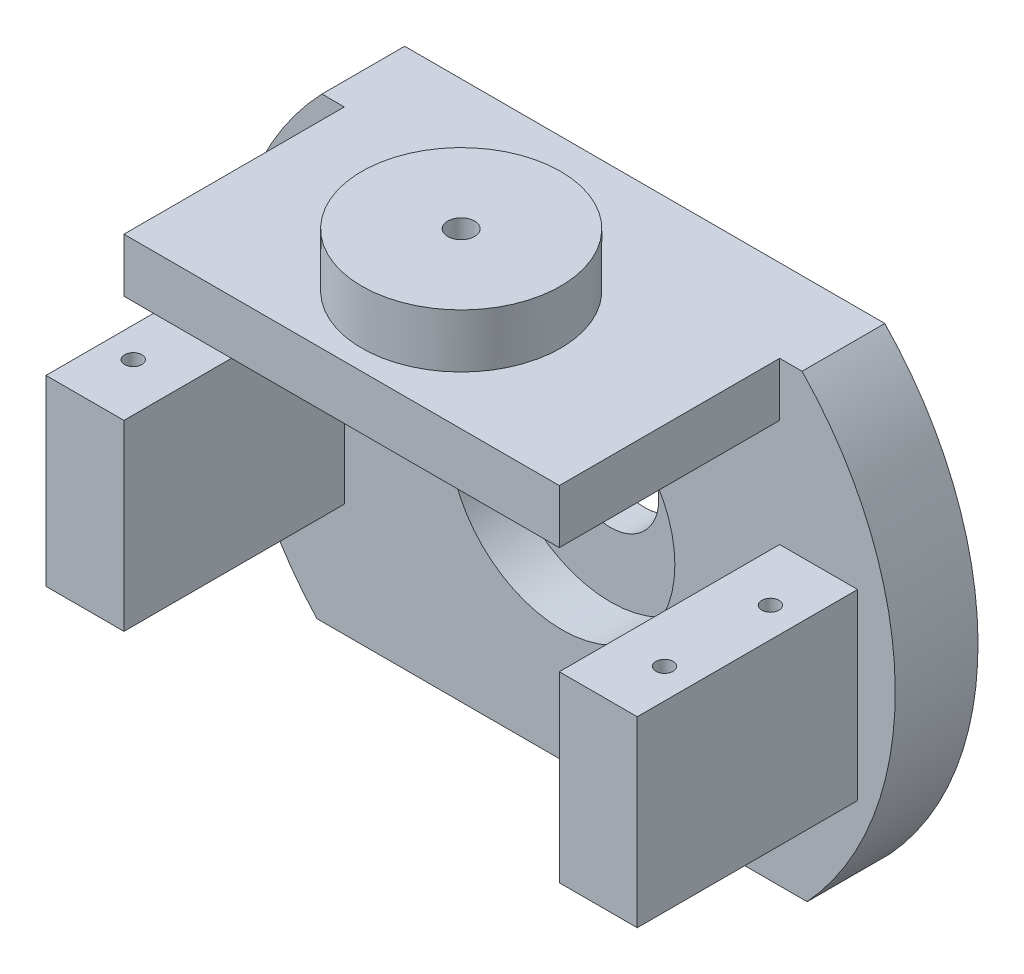
SolidWorks part; units mm, degrees
ref_plane "Plan de face" through (0, 0, 0) normal (0, 0, 1) x (1, 0, 0)
ref_plane "Plan de dessus" through (0, 0, 0) normal (0, 1, 0) x (1, 0, 0)
ref_plane "Plan de droite" through (0, 0, 0) normal (1, 0, 0) x (0, 0, -1)
sketch "Esquisse1" plane through (0, 0, 0) normal (0, 0, 1) x (1, 0, 0)
  line L1 (-27.5, 21.5) -> (27.5, 21.5)
  line L2 (-27.5, 21.5) -> (-27.5, -21.5)
  line L3 (-27.5, -21.5) -> (27.5, -21.5)
  line L4 (27.5, 21.5) -> (27.5, -21.5)
  line L5 (-27.5, 21.5) -> (27.5, -21.5) construction
  line L6 (-27.5, -21.5) -> (27.5, 21.5) construction
  point P0 (0, 0)
  dimension "D1" = 55
  dimension "D2" = 43
extrude "Boss.-Extru.1" add sketch "Esquisse1" along normal blind 27
sketch "Esquisse2" plane through (0, -21.5, 0) normal (0, -1, 0) x (1, 0, 0)
  line L0 (27.5, 27) -> (27.5, 0) construction
  line L1 (-27.5, 0) -> (27.5, 0) construction
  line L2 (-27.5, 0) -> (-27.5, 6.5) construction
  line L3 (-27.5, 6.5) -> (27.5, 6.5) construction
  line L4 (27.5, 0) -> (27.5, 6.5) construction
  line L5 (0, 0) -> (0, 33.905) construction
  line L6 (-20.25, 6.5) -> (20.25, 6.5)
  line L7 (-20.25, 6.5) -> (-20.25, 28.1766)
  line L8 (-20.25, 28.1766) -> (20.25, 28.1766)
  line L9 (20.25, 6.5) -> (20.25, 28.1766)
  dimension "D1" = 6.5
  dimension "D2" = 40.5
extrude "Enlèv. mat.-Extru.1" cut sketch "Esquisse2" against normal offset from surface (38 mm away) 5 up to face at (0, 21.5, 13.5)
sketch "Esquisse3" plane through (0, -21.5, 0) normal (0, -1, 0) x (1, 0, 0)
  line L0 (-20.25, 16.75) -> (28.5647, 16.75) construction
  line L1 (-20.25, 6.5) -> (-20.25, 27) construction
  line L2 (0, 27) -> (0, -2.6321) construction
  line L3 (-20.25, 27) -> (20.25, 27) construction
  line L4 (-20.25, 27) -> (-20.25, 6.5) construction
  circle A0 centre (-24.71, 21.675) radius 0.7
  circle A2 centre (-24.71, 11.825) radius 0.7
  circle A3 centre (24.71, 11.825) radius 0.7
  circle A4 centre (24.71, 21.675) radius 0.7
  point P9 (-24.71, 21.675)
  point P12 (-24.71, 11.825)
  point P13 (24.71, 11.825)
  point P14 (24.71, 21.675)
  dimension "D4" = 1.4
  dimension "D1" = 4.46
  dimension "D2" = 4.925
  dimension "D3" = 9.85
extrude "Enlèv. mat.-Extru.2" cut sketch "Esquisse3" against normal up to surface (43 mm away) up to face at (0, 21.5, 13.5)
sketch "Esquisse4" plane through (0, -21.5, 0) normal (0, -1, 0) x (1, 0, 0)
  line L0 (27.5, 27) -> (27.5, 0) construction
  line L1 (-27.5, 27) -> (27.5, 27)
  line L2 (-27.5, 27) -> (-27.5, 6.5)
  line L3 (-27.5, 6.5) -> (27.5, 6.5)
  line L4 (27.5, 27) -> (27.5, 6.5)
extrude "Enlèv. mat.-Extru.3" cut sketch "Esquisse4" against normal offset from surface (11 mm away) 27 up to face at (0, 16.5, 16.75)
sketch "Esquisse5" plane through (-27.5, 0, 0) normal (-1, 0, 0) x (0, 0, 1)
  line L6 (6.5, 16.5) -> (27, 16.5)
  line L7 (6.5, 16.5) -> (6.5, 6.5)
  line L8 (6.5, 6.5) -> (27, 6.5)
  line L9 (27, 16.5) -> (27, 6.5)
  line L10 (27, 21.5) -> (27, -10.5) construction
  line L11 (27, 21.5) -> (0, 21.5) construction
  line L13 (6.5, -10.5) -> (6.5, -21.5) construction
  point P4 (0, 0)
  point P12 (0, 0)
  dimension "D1" = 5
  dimension "D2" = 10
extrude "Enlèv. mat.-Extru.6" cut sketch "Esquisse5" against normal up to surface (55 mm away) up to face at (27.5, -3.5, 11.1667)
sketch "Esquisse6" plane through (0, 16.5, 0) normal (0, -1, 0) x (1, 0, 0)
  line L1 (-27.5, 27) -> (-20.25, 27)
  line L2 (-27.5, 27) -> (-27.5, 6.5)
  line L3 (-27.5, 6.5) -> (-20.25, 6.5)
  line L4 (-20.25, 27) -> (-20.25, 6.5)
  line L5 (20.25, 27) -> (27.5, 27)
  line L6 (20.25, 27) -> (20.25, 6.5)
  line L7 (20.25, 6.5) -> (27.5, 6.5)
  line L8 (27.5, 27) -> (27.5, 6.5)
extrude "Enlèv. mat.-Extru.7" cut sketch "Esquisse6" against normal up to surface (5 mm away) up to face at (24.71, 21.5, 20.975)
sketch "Esquisse7" plane through (0, 0, 0) normal (0, 0, -1) x (-1, 0, 0)
  circle A0 centre (0, 0) radius 31
  dimension "D1" = 62
extrude "Boss.-Extru.2" add sketch "Esquisse7" against normal up to surface (6.5 mm away) up to face at (0, 3.75, 6.5)
sketch "Esquisse8" plane through (0, 0, 0) normal (0, 0, -1) x (-1, 0, 0)
  circle A0 centre (0, 0) radius 31
  circle A1 centre (0, 0) radius 41
  arc A2 (22.3327, 21.5) -> (-22.3327, 21.5) centre (0, 0) ccw construction
  dimension "D1" = 62
  dimension "D2" = 82
extrude "Enlèv. mat.-Extru.8" cut sketch "Esquisse8" against normal up to surface (6.5 mm away) up to face at (0, 0, 6.5)
hole_wizard "Trou taraudé M2x0.41" positions "Esquisse3D1" profile "Esquisse9" tap size "M2x0.4" standard "Ansi Metric" end condition through all
sketch3d "Esquisse3D1"
  line L0 (-24.71, 6.5, 21.675) -> (-24.71, -10.5, 21.675) construction
  line L1 (-24.71, 6.5, 11.825) -> (-24.71, -10.5, 11.825) construction
  line L2 (24.71, 6.5, 21.675) -> (24.71, -10.5, 21.675) construction
  line L3 (24.71, 6.5, 11.825) -> (24.71, -10.5, 11.825) construction
  point P0 (-24.71, -10.5, 21.675)
  point P4 (-24.71, -10.5, 11.825)
  point P8 (24.71, -10.5, 21.675)
  point P12 (24.71, -10.5, 11.825)
sketch "Esquisse9" plane through (-24.71, -10.5, 21.675) normal (1, 0, 0) x (0, 0, -1)
  line L0 (0, 0) -> (0, 41.5)
  line L1 (0, 41.5) -> (0.8, 41.5)
  line L2 (0.8, 41.5) -> (0.8, 0)
  line L5 (0.8, 0) -> (0, 0)
  line L11 (0, -6.35) -> (0, 107.95) construction
  dimension "Diamètre du trou pour taraudage jusqu'au prochain" = 1.6
  dimension "Profondeur du trou pour taraudage jusqu'au prochain" = 41.5
cosmetic thread "Filetage de perçage1" parameters "D2"=2
cosmetic thread "Filetage de perçage2" parameters "D2"=2
cosmetic thread "Filetage de perçage3" parameters "D2"=2
cosmetic thread "Filetage de perçage4" parameters "D2"=2
sketch "Esquisse10" plane through (0, 0, 6.5) normal (0, 0, 1) x (1, 0, 0)
  circle A0 centre (0, 0) radius 10.5
  dimension "D1" = 21
extrude "Enlèv. mat.-Extru.9" cut sketch "Esquisse10" against normal offset from surface (4.5 mm away) 2 up to face at (-31, 0, 0)
sketch "Esquisse11" plane through (0, 0, 2) normal (0, 0, 1) x (1, 0, 0)
  circle A0 centre (0, 0) radius 4.5
  dimension "D1" = 9
extrude "Enlèv. mat.-Extru.10" cut sketch "Esquisse11" against normal up to surface (2 mm away) up to face at (-31, 0, 0)
sketch "Esquisse12" plane through (0, 21.5, 0) normal (0, 1, 0) x (1, 0, 0)
  line L0 (0, 0) -> (0, -31.7536) construction
  circle A0 centre (0, -15.8768) radius 9.25
  circle A1 centre (0, -15.8768) radius 1.25
  dimension "D1" = 18.5
  dimension "D2" = 2.5
extrude "Boss.-Extru.3" add sketch "Esquisse12" along normal blind 5
sketch "Esquisse13" plane through (0, 0, 6.5) normal (0, 0, 1) x (1, 0, 0)
  line L0 (-26.0408, 21.5) -> (24.0741, 21.5)
  line L1 (24.0741, 21.5) -> (24.0741, 33.5126)
  line L2 (24.0741, 33.5126) -> (-26.0408, 33.5126)
  line L3 (-26.0408, 33.5126) -> (-26.0408, 21.5)
extrude "Enlèv. mat.-Extru.11" cut sketch "Esquisse13" against normal up to surface (6.5 mm away) up to face at (4.5, 0, 0)
sketch "Esquisse14" plane through (0, 0, 0) normal (0, 0, -1) x (-1, 0, 0)
  line L0 (-22.3327, 21.5) -> (22.3327, 21.5) construction
  line L1 (-22.3327, 21.5) -> (22.3327, 21.5)
  arc A0 (-22.3327, 21.5) -> (22.3327, 21.5) centre (0, 0) ccw construction
  arc A1 (-22.3327, 21.5) -> (22.3327, 21.5) centre (0, 0) ccw
extrude "Boss.-Extru.4" add sketch "Esquisse14" along normal blind 1.2
sketch "Esquisse15" plane through (0, 0, 6.5) normal (0, 0, 1) x (1, 0, 0)
  line L0 (0, 0) -> (0, -35.7271) construction
  line L1 (26.5027, -31) -> (-26.5027, -31)
  line L2 (26.5027, -31) -> (26.5027, -21)
  line L3 (26.5027, -21) -> (-26.5027, -21)
  line L4 (-26.5027, -31) -> (-26.5027, -21)
  arc A0 (-22.3327, 21.5) -> (22.3327, 21.5) centre (0, 0) ccw construction
  dimension "D1" = 10
extrude "Enlèv. mat.-Extru.12" cut sketch "Esquisse15" against normal up to surface (7.7 mm away) up to face at (0, -4.75, -1.2)
sketch "Esquisse16" plane through (0, 0, 0) normal (0, 0, 1) x (1, 0, 0)
  circle A0 centre (0, 0) radius 4.5
extrude "Enlèv. mat.-Extru.13" cut sketch "Esquisse16" against normal up to surface (1.2 mm away) up to face at (0, 0.2967, -1.2)
equation "\"1c\"=0.00309185"
equation "\"D2@Esquisse8\"=\"D1@Esquisse8\"+2cm"
